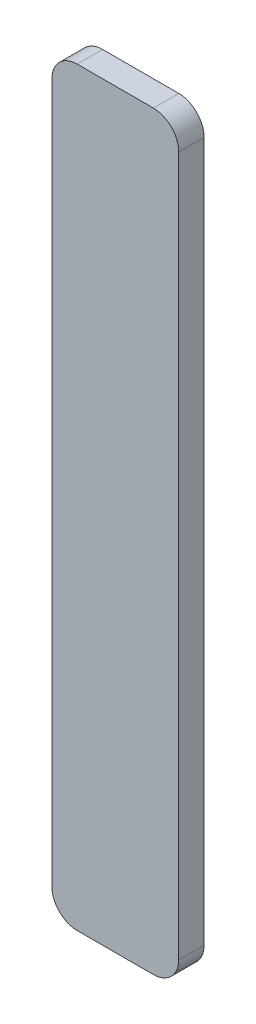
SolidWorks part; units mm, degrees
ref_plane "Front Plane" through (0, 0, 0) normal (0, 0, 1) x (1, 0, 0)
ref_plane "Top Plane" through (0, 0, 0) normal (0, 1, 0) x (1, 0, 0)
ref_plane "Right Plane" through (0, 0, 0) normal (1, 0, 0) x (0, 0, -1)
sketch "Sketch1" plane through (0, 0, 0) normal (0, 0, 1) x (1, 0, 0)
  line L0 (-2.5, 28.58) -> (-2.5, 1)
  line L1 (-1.5, 0) -> (1.5, 0)
  line L2 (-1.5, 29.58) -> (1.5, 29.58)
  line L3 (0, 8.4408) -> (0, 50.6564) construction
  line L4 (2.5, 28.58) -> (2.5, 1)
  arc A0 (-2.5, 1) -> (-1.5, 0) centre (-1.5, 1) ccw
  arc A1 (-2.5, 28.58) -> (-1.5, 29.58) centre (-1.5, 28.58) cw
  arc A2 (2.5, 28.58) -> (1.5, 29.58) centre (1.5, 28.58) ccw
  arc A3 (2.5, 1) -> (1.5, 0) centre (1.5, 1) cw
  point P8 (0, 0)
  point P19 (0, 29.58)
  dimension "D3" = 1
  dimension "D1" = 29.58
  dimension "D2" = 5
extrude "Boss-Extrude1" add sketch "Sketch1" along normal blind 1
equation "\"PCBWidth\" = 5"
equation "\"BearingBaseDistance\"= 12"
equation "\"BearingOD\"= 32"
equation "\"BearingID\" = 25"
equation "\"BearingHeight\"= 4"
equation "\"SeatsOD\"= \"BearingOD\" + 10"
equation "\"WireHarnessHeight\"= 0.05in * 4 + 4.5"
equation "\"OuterWallWidth\"= 6"
equation "\"OverallOD\" = 50"
equation "\"OuterHousingHeight\" = \"WireHarnessHeight\" + \"BearingHeight\"*2 + \"BearingBaseDistance\""
equation "\"RetainingRingThickness\" = 1.30"
equation "\"RetaininRingGrooveDiameter\" = 23.9"
equation "\"ShaftLengthAfterFlange\" = 2*\"BearingHeight\" + \"BearingBaseDistance\" + \"RetainingRingThickness\"*2\t'give a retaining ring thickness of extra clearance"
equation "\"RetainingRingGrooveBase\" = \"ShaftLengthAfterFlange\" - \"RetainingRingThickness\"*2"
equation "\"CoverThickness\" = 1"
equation "\"PCBHeight\" = \"OuterHousingHeight\" "
equation "\"CoverClearance\" = 1"
equation "\"FlangHeight\" = \"CoverThickness\" + \"CoverClearance\" + \"WireHarnessHeight\""
equation "\"PCBThickness\" = 1"
equation "\"D1@Boss-Extrude1\"=\"PCBThickness\""
equation "\"D1@Sketch1\"=\"PCBHeight\""
equation "\"D2@Sketch1\"=\"PCBWidth\""
